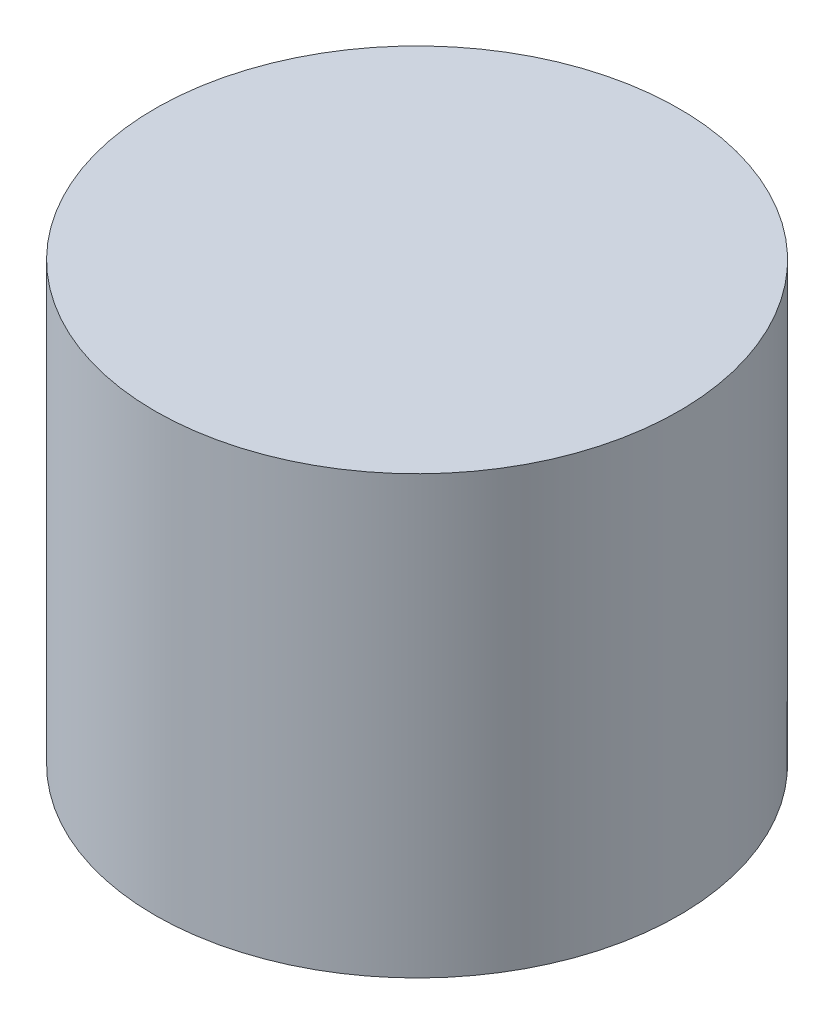
SolidWorks part; units mm, degrees
ref_plane "前视基准面" through (0, 0, 0) normal (0, 0, 1) x (1, 0, 0)
ref_plane "上视基准面" through (0, 0, 0) normal (0, 1, 0) x (1, 0, 0)
ref_plane "右视基准面" through (0, 0, 0) normal (1, 0, 0) x (0, 0, -1)
other "Configuration Table"
sketch "草图1" plane through (0, 0, 0) normal (0, 1, 0) x (1, 0, 0)
  circle A0 centre (12.5, -12.5) radius 15
extrude "凸台-拉伸1" add sketch "草图1" along normal blind 25
